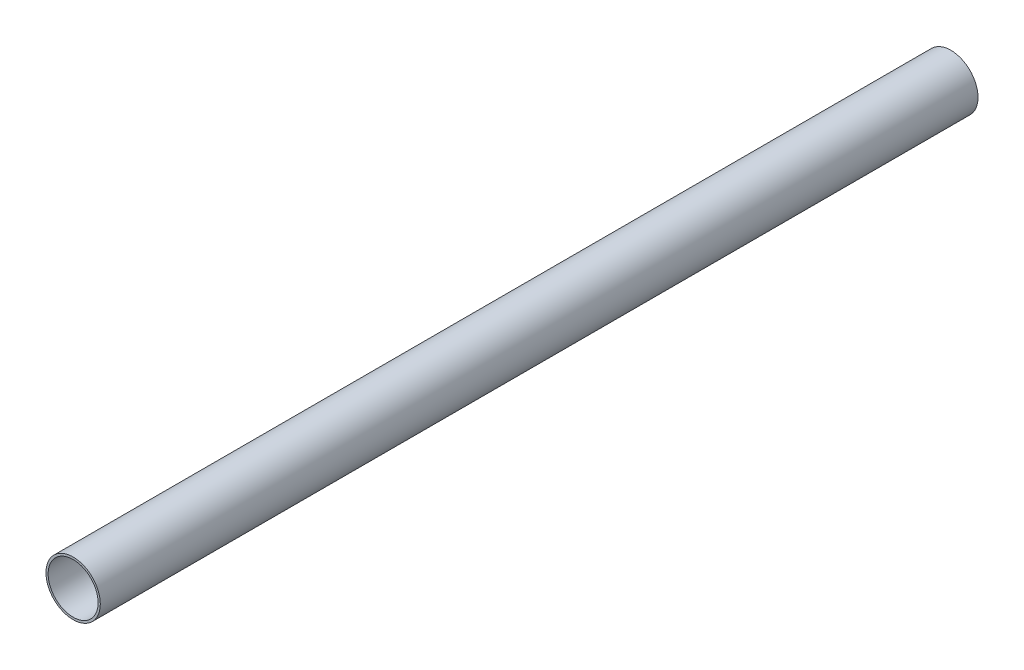
SolidWorks part; units mm, degrees
material "PC High Viscosity"
ref_plane "Front Plane" through (0, 0, 0) normal (0, 0, 1) x (1, 0, 0)
ref_plane "Top Plane" through (0, 0, 0) normal (0, 1, 0) x (1, 0, 0)
ref_plane "Right Plane" through (0, 0, 0) normal (1, 0, 0) x (0, 0, -1)
sketch "Sketch1" plane through (0, 0, 0) normal (0, 0, 1) x (1, 0, 0)
  circle A0 centre (0, 0) radius 12.5
  circle A1 centre (0, 0) radius 11.5
  dimension "D1" = 25
  dimension "D2" = 1
extrude "Boss-Extrude1" add sketch "Sketch1" along normal blind 403.72
